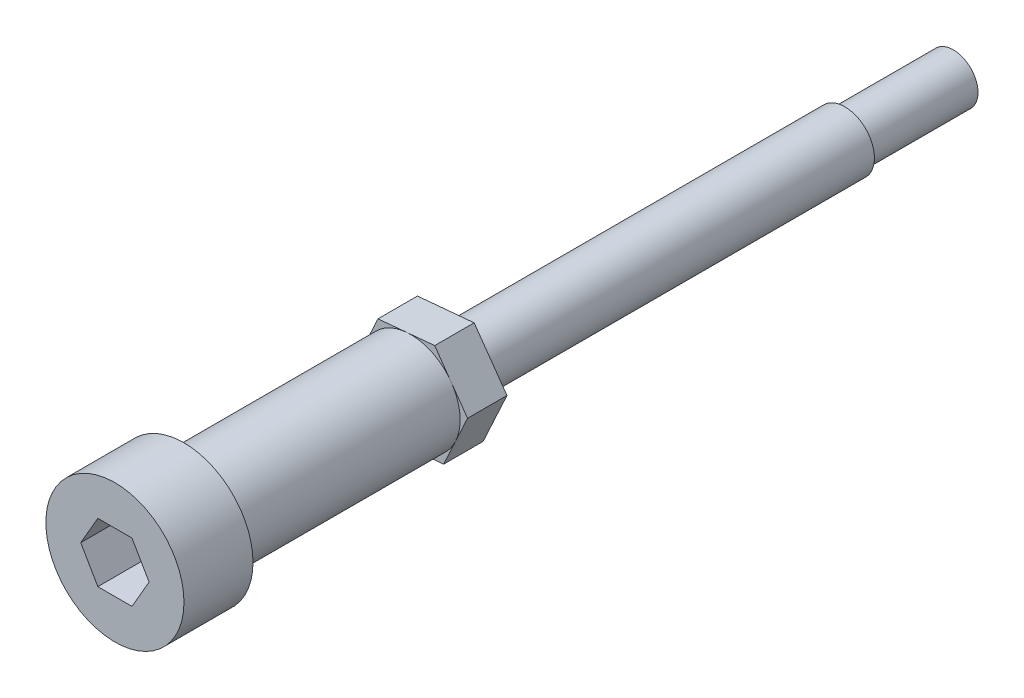
SolidWorks part; units mm, degrees
ref_plane "Plan1" through (0, 0, 0) normal (0, 0, 1) x (1, 0, 0)
ref_plane "Plan2" through (0, 0, 0) normal (0, 1, 0) x (1, 0, 0)
ref_plane "Plan3" through (0, 0, 0) normal (1, 0, 0) x (0, 0, -1)
sketch "Esquisse2" plane through (0, 0, 0) normal (1, 0, 0) x (0, 0, -1)
  line L0 (-67, 0) -> (120, 0) construction
  line L1 (0, 0) -> (0, 14)
  line L2 (0, 14) -> (14, 14)
  line L3 (14, 14) -> (14, 10)
  line L4 (14, 10) -> (60, 10)
  line L5 (60, 10) -> (60, 6)
  line L6 (60, 6) -> (148, 6)
  line L7 (148, 6) -> (148, 5)
  line L8 (148, 5) -> (170, 5)
  line L9 (170, 5) -> (170, 0)
  line L10 (0, 0) -> (170, 0)
  dimension "D1" = 14
  dimension "D2" = 46
  dimension "D3" = 88
  dimension "D4" = 22
  dimension "D5" = 14
  dimension "D6" = 10
  dimension "D7" = 6
  dimension "D8" = 5
revolve "Base-Révolution" add sketch "Esquisse2" angle 360 about L0
sketch "Esquisse3" plane through (0, 0, 0) normal (0, 0, 1) x (1, 0, 0)
  line L1 (6.9282, 0) -> (3.4641, 6)
  line L2 (3.4641, 6) -> (-3.4641, 6)
  line L3 (-3.4641, 6) -> (-6.9282, 0)
  line L4 (-6.9282, 0) -> (-3.4641, -6)
  line L5 (-3.4641, -6) -> (3.4641, -6)
  line L6 (3.4641, -6) -> (6.9282, 0)
  circle A0 centre (0, 0) radius 6 construction
  dimension "D1" = 12
extrude "Enlèv. mat.-Extru.1" cut sketch "Esquisse3" against normal blind 10
sketch "Esquisse5" plane through (0, 0, -60) normal (0, 0, -1) x (-1, 0, 0)
  circle A0 centre (0, 0) radius 6 construction
  circle A1 centre (0, 0) radius 6
sketch "Esquisse7" plane through (0, 0, -60) normal (0, 0, -1) x (-1, 0, 0)
  line L1 (4.8389, -10.4842) -> (11.499, -1.0515)
  line L2 (11.499, -1.0515) -> (6.6602, 9.4327)
  line L3 (6.6602, 9.4327) -> (-4.8389, 10.4842)
  line L4 (-4.8389, 10.4842) -> (-11.499, 1.0515)
  line L5 (-11.499, 1.0515) -> (-6.6602, -9.4327)
  line L6 (-6.6602, -9.4327) -> (4.8389, -10.4842)
  circle A0 centre (0, 0) radius 10 construction
  circle A1 centre (0, 0) radius 10 construction
extrude "Boss.-Extru.1" add sketch "Esquisse7" along normal blind 8
curve "Hélice1" pitch 5 height 90 turns 18
